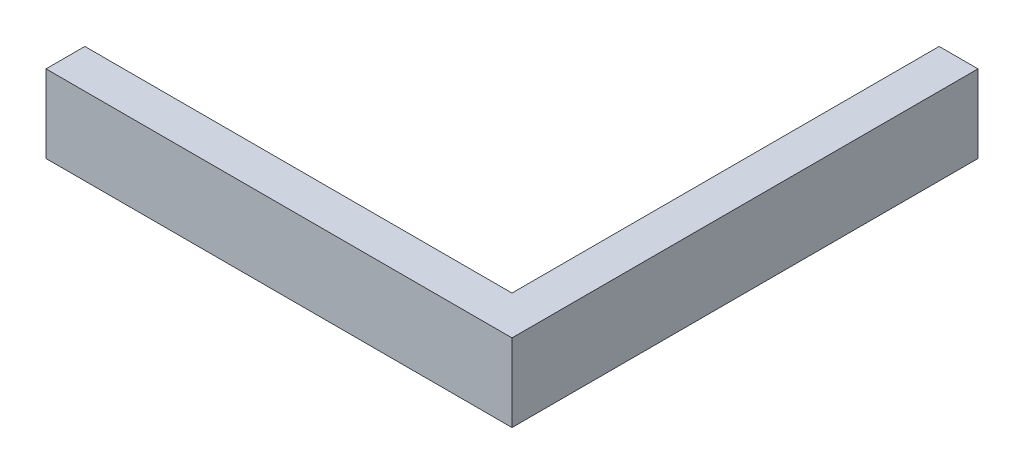
SolidWorks part; units mm, degrees
ref_plane "Front Plane" through (0, 0, 0) normal (0, 0, 1) x (1, 0, 0)
ref_plane "Top Plane" through (0, 0, 0) normal (0, 1, 0) x (1, 0, 0)
ref_plane "Right Plane" through (0, 0, 0) normal (1, 0, 0) x (0, 0, -1)
sketch "Sketch1" plane through (0, 0, 0) normal (0, 1, 0) x (1, 0, 0)
  line L1 (30, -30) -> (-30, -30)
  line L2 (30, -30) -> (30, 30)
  line L3 (30, 30) -> (-30, 30)
  line L4 (-30, -30) -> (-30, 30)
  line L5 (30, -30) -> (-30, 30) construction
  line L6 (30, 30) -> (-30, -30) construction
  point P0 (0, 0)
  dimension "D1" = 60
  dimension "D2" = 60
extrude "Boss-Extrude1" add sketch "Sketch1" along normal blind 10
sketch "Sketch2" plane through (0, 10, 0) normal (0, 1, 0) x (1, 0, 0)
  line L1 (-30, 30) -> (25, 30)
  line L2 (-30, 30) -> (-30, -25)
  line L3 (-30, -25) -> (25, -25)
  line L4 (25, 30) -> (25, -25)
  dimension "D1" = 55
extrude "Cut-Extrude1" cut sketch "Sketch2" against normal through all
